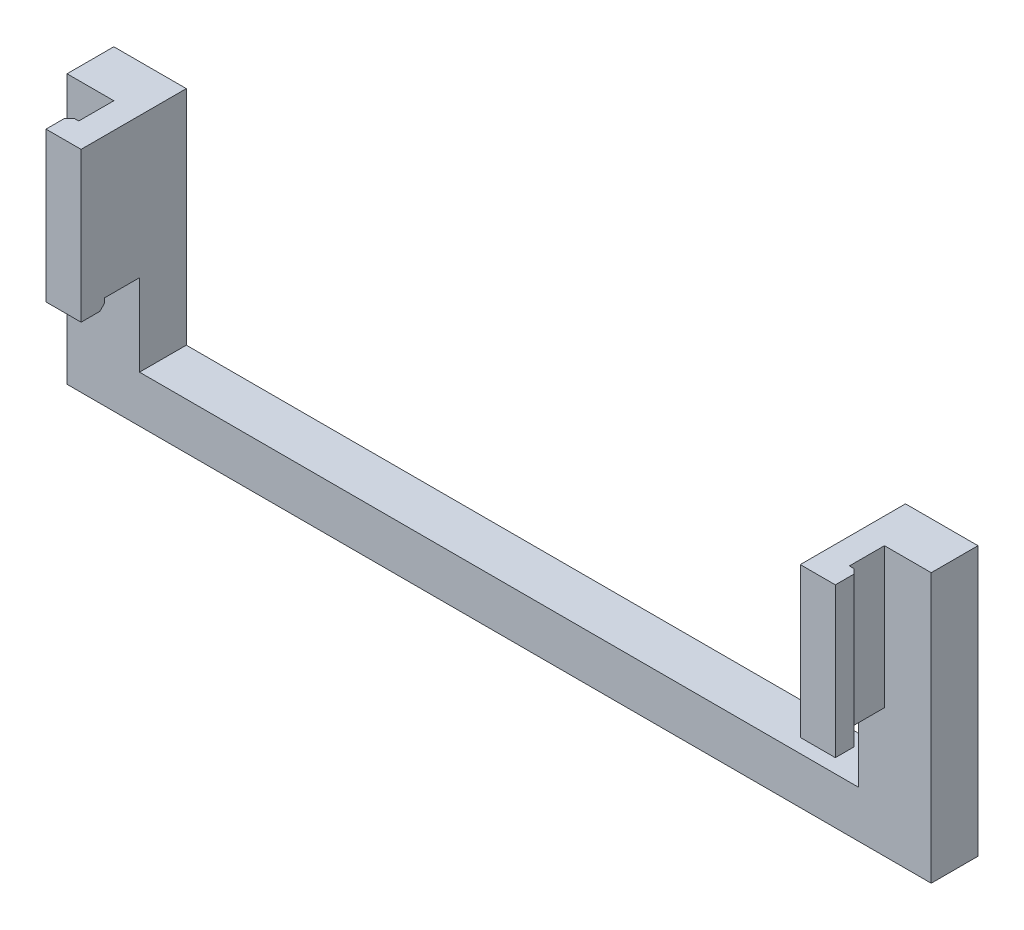
SolidWorks part; units mm, degrees
ref_plane "Front Plane" through (0, 0, 0) normal (0, 0, 1) x (1, 0, 0)
ref_plane "Top Plane" through (0, 0, 0) normal (0, 1, 0) x (1, 0, 0)
ref_plane "Right Plane" through (0, 0, 0) normal (1, 0, 0) x (0, 0, -1)
sketch "Sketch1" plane through (0, 0, 0) normal (0, 0, -1) x (-1, 0, 0)
  line L2 (-262.9558, 81.4554) -> (-266.0559, 81.4554)
  line L3 (-266.0559, 81.4554) -> (-266.0559, 71.9547)
  line L8 (-299.907, 69.9547) -> (-262.9558, 69.9547)
  line L9 (-262.9558, 69.9547) -> (-262.9558, 81.4554)
  line L10 (-262.9558, 84.9556) -> (-262.9558, 91.9547) construction
  line L11 (-265.3309, 81.9554) -> (-266.1559, 81.9554) construction
  line L12 (-266.1559, 81.9554) -> (-266.1559, 75.6847) construction
  line L13 (-266.0559, 71.9547) -> (-273.0063, 71.9547)
  line L22 (-299.907, 69.9547) -> (-299.907, 81.4554)
  line L23 (-264.9058, 75.4547) -> (-267.88, 75.4547) construction
  line L24 (-296.8069, 81.4554) -> (-296.8069, 71.9547)
  line L26 (-296.8069, 71.9547) -> (-273.0063, 71.9547)
  line L29 (-296.8069, 81.4554) -> (-299.907, 81.4554)
  point P38 (-281.4314, 69.9547)
  dimension "D1" = 0.5
  dimension "D2" = 0.1
  dimension "D7" = 2
  dimension "D8" = 3.5
extrude "Boss-Extrude1" add sketch "Sketch1" along normal up to surface (2 mm away)
sketch "Sketch2" plane through (0, 0, 0) normal (0, 0, 1) x (1, 0, 0)
  line L0 (264.9058, 75.4547) -> (267.88, 75.4547) construction
  line L1 (266.0559, 81.4554) -> (264.9558, 81.4554)
  line L2 (266.0559, 81.4554) -> (266.0559, 75.4547)
  line L3 (266.0559, 75.4547) -> (264.9558, 75.4547)
  line L4 (264.9558, 81.4554) -> (264.9558, 75.4547)
  line L10 (271.1802, 75.4547) -> (291.6806, 75.4547) construction
  line L11 (264.9058, 89.4547) -> (264.9058, 75.4547) construction
  line L12 (281.4314, 75.4547) -> (281.4314, 89.4547) construction
  line L13 (274.4314, 75.4547) -> (288.4314, 75.4547) construction
  line L14 (288.4314, 89.4547) -> (274.4314, 89.4547) construction
  line L19 (296.8069, 75.4547) -> (297.907, 75.4547)
  line L20 (297.907, 81.4554) -> (297.907, 75.4547)
  line L21 (296.8069, 81.4554) -> (297.907, 81.4554)
  line L22 (296.8069, 81.4554) -> (296.8069, 75.4547)
  dimension "D1" = 0.05
extrude "Boss-Extrude2" add sketch "Sketch2" along normal up to surface (1.5 mm away)
sketch "Sketch3" plane through (0, 0, 1.5) normal (0, 0, 1) x (1, 0, 0)
  line L0 (264.9558, 75.4547) -> (266.0559, 75.4547) construction
  line L1 (266.0559, 81.4554) -> (264.5558, 81.4554)
  line L2 (266.0559, 81.4554) -> (266.0559, 75.0547)
  line L3 (266.0559, 75.0547) -> (264.5558, 75.0547)
  line L4 (264.5558, 81.4554) -> (264.5558, 75.0547)
  line L5 (264.9558, 81.4554) -> (264.9558, 75.4547) construction
  line L6 (281.4314, 89.4547) -> (281.4314, 75.4547) construction
  line L7 (264.9058, 89.4547) -> (297.957, 89.4547) construction
  line L8 (274.4314, 75.4547) -> (288.4314, 75.4547) construction
  line L9 (296.8069, 75.0547) -> (298.307, 75.0547)
  line L10 (298.307, 81.4554) -> (298.307, 75.0547)
  line L11 (296.8069, 81.4554) -> (298.307, 81.4554)
  line L12 (296.8069, 81.4554) -> (296.8069, 75.0547)
  dimension "D1" = 0.4
  dimension "D2" = 0.4
extrude "Boss-Extrude3" add sketch "Sketch3" along normal up to surface (1 mm away)
chamfer "Chamfer1" distance 0.2 angle 45 4 edges at (298.307, 78.2551, 1.5) (297.557, 75.0547, 1.5) (265.3059, 75.0547, 1.5) (264.5558, 78.2551, 1.5)
